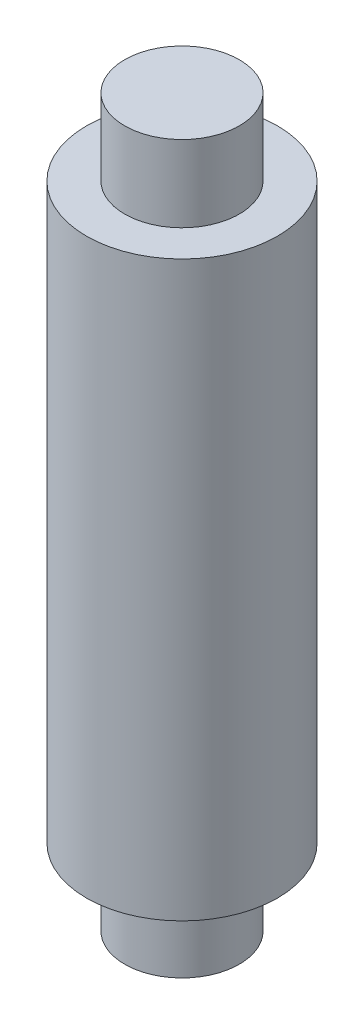
SolidWorks part; units mm, degrees
ref_plane "Front Plane" through (0, 0, 0) normal (0, 0, 1) x (1, 0, 0)
ref_plane "Top Plane" through (0, 0, 0) normal (0, 1, 0) x (1, 0, 0)
ref_plane "Right Plane" through (0, 0, 0) normal (1, 0, 0) x (0, 0, -1)
sketch "Sketch1" plane through (0, 0, 0) normal (0, 0, 1) x (1, 0, 0)
  line L0 (0, -11.6601) -> (0, -30.6601)
  line L1 (0, -30.6601) -> (-1.5, -30.6601)
  line L2 (-1.5, -30.6601) -> (-1.5, -28.6601)
  line L3 (-1.5, -28.6601) -> (-2.5, -28.6601)
  line L4 (-2.5, -28.6601) -> (-2.5, -13.6601)
  line L5 (-2.5, -13.6601) -> (-1.5, -13.6601)
  line L6 (-1.5, -13.6601) -> (-1.5, -11.6601)
  line L7 (-1.5, -11.6601) -> (0, -11.6601)
  dimension "D1" = 2
  dimension "D2" = 2.5
  dimension "D3" = 1.5
  dimension "D4" = 1.5
  dimension "D5" = 15
  dimension "D6" = 2
revolve "Revolve1" add sketch "Sketch1" angle 360 about L0
